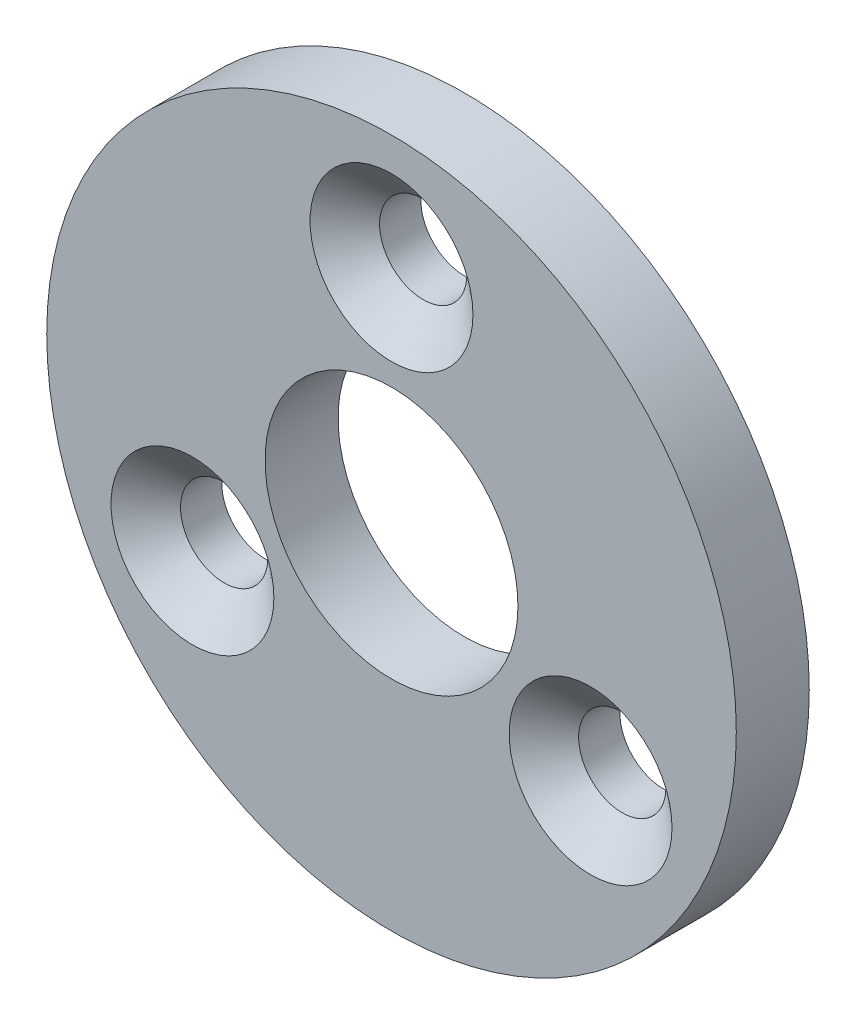
SolidWorks part; units mm, degrees
material "Nickel"
ref_plane "Front Plane" through (0, 0, 0) normal (0, 0, 1) x (1, 0, 0)
ref_plane "Top Plane" through (0, 0, 0) normal (0, 1, 0) x (1, 0, 0)
ref_plane "Right Plane" through (0, 0, 0) normal (1, 0, 0) x (0, 0, -1)
sketch "Sketch1" plane through (0, 0, 0) normal (0, 0, 1) x (1, 0, 0)
  circle A0 centre (0, 0) radius 15
  circle A1 centre (0, 0) radius 5.5
extrude "Body" add sketch "Sketch1" along normal blind 3.175
hole_wizard "CSK for #6 Flat Head Machine Screw (100)1" positions "3DSketch2" profile "Sketch3" countersink size "#6" standard "Ansi Inch" end condition through all
sketch3d "3DSketch2"
  line L0 (0, 15, 3.175) -> (0, 0, 3.175) construction
  line L1 (0, 0, 3.175) -> (0, 0, 0) construction
  line L2 (0, 0, 3.175) -> (0, 0, 0) construction
  line L3 (0, 0, 3.175) -> (-12.9904, -7.5, 3.175) construction
  line L4 (0, 0, 3.175) -> (12.9904, -7.5, 3.175) construction
  circle A0 centre (0, 0, 3.175) radius 15 construction
  circle A1 centre (0, 0, 3.175) radius 10
  point P0 (0, 10, 3.175)
  point P2 (-8.6603, -5, 3.175)
  point P4 (8.6603, -5, 3.175)
  point P11 (0, 0, 18.175)
  point P23 (0, 0, 13.175)
  dimension "D3" = 20
  dimension "D1" = 120
  dimension "D2" = 120
sketch "Sketch3" plane through (0, 10, 3.175) normal (1, 0, 0) x (0, -1, 0)
  line L0 (0, 0) -> (0, 3.175)
  line L1 (0, 3.175) -> (1.8986, 3.175)
  line L2 (1.8986, 3.175) -> (1.8986, 1.38)
  line L3 (1.8986, 1.38) -> (3.5433, 0)
  line L5 (3.5433, 0) -> (0, 0)
  line L6 (-1.8986, 1.38) -> (-3.5433, 0) construction
  line L11 (0, -6.35) -> (0, 107.95) construction
  dimension "Thru Hole Dia." = 3.7973
  dimension "Thru Hole Depth" = 3.175
  dimension "Near C'Sink Dia." = 7.0866
  dimension "Near C'Sink Angle" = 100
